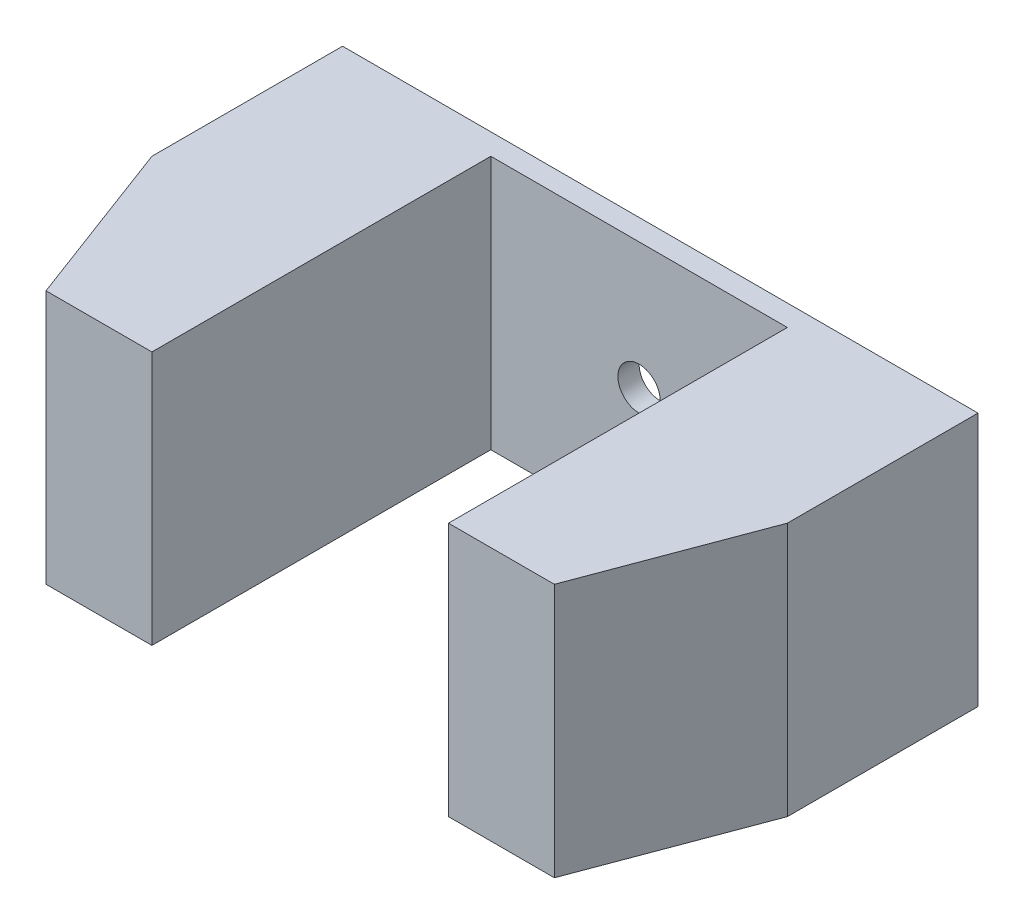
SolidWorks part; units mm, degrees
material "ABS"
ref_plane "Front Plane" through (0, 0, 0) normal (0, 0, 1) x (1, 0, 0)
ref_plane "Top Plane" through (0, 0, 0) normal (0, 1, 0) x (1, 0, 0)
ref_plane "Right Plane" through (0, 0, 0) normal (1, 0, 0) x (0, 0, -1)
sketch "Sketch1" plane through (0, 0, 0) normal (0, 0, 1) x (1, 0, 0)
  line L0 (0, 30) -> (0, -30) construction
  line L1 (-75, 30) -> (75, 30)
  line L2 (-75, 30) -> (-75, -30)
  line L3 (-75, -30) -> (75, -30)
  line L4 (75, 30) -> (75, -30)
  line L5 (75, 0) -> (-75, 0) construction
  circle A0 centre (0, 0) radius 5
  dimension "D2" = 60
  dimension "D1" = 150
extrude "Boss-Extrude1" add sketch "Sketch1" along normal blind 5 contours L2 L3 L4 L1 | A0
sketch "Sketch2" plane through (0, 30, 0) normal (0, 1, 0) x (1, 0, 0)
  line L1 (-35, -85) -> (-35, -5)
  line L2 (-75, -5) -> (75, -5) construction
  line L3 (-75, -5) -> (-35, -5)
  line L4 (-75, -5) -> (-75, -45)
  line L5 (-75, -45) -> (-60, -85)
  line L6 (-60, -85) -> (-35, -85)
  point P3 (-75, -44.6614)
  dimension "D1" = 80
  dimension "D2" = 40
  dimension "D3" = 25
  dimension "D4" = 40
extrude "Boss-Extrude2" add sketch "Sketch2" against normal up to surface (60 mm away) contours L4 L5 L6 L1 L3 up to face at (0, -30, 2.5)
mirror "Mirror1" about plane through (0, 0, 0) normal (1, 0, 0) of "Boss-Extrude2"
